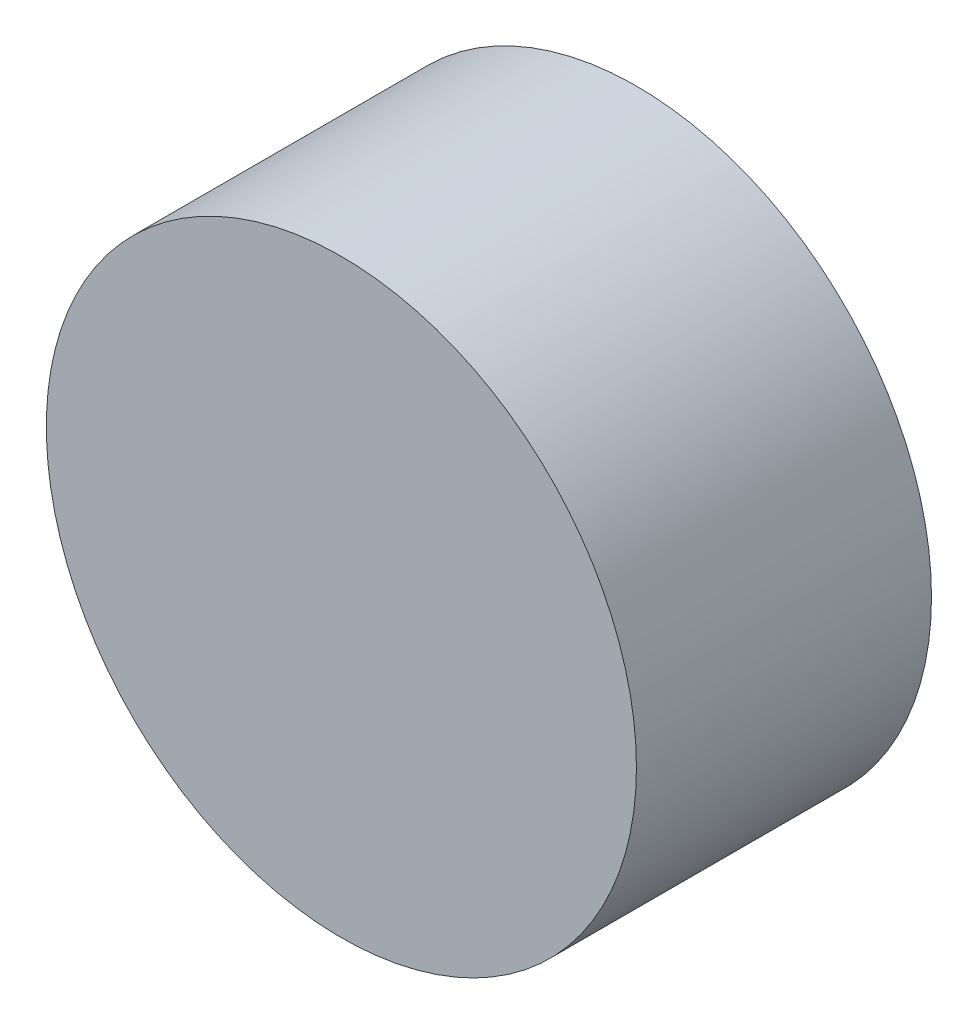
SolidWorks part; units mm, degrees
material "AISI 304"
ref_plane "Plan de face" through (0, 0, 0) normal (0, 0, 1) x (1, 0, 0)
ref_plane "Plan de dessus" through (0, 0, 0) normal (0, 1, 0) x (1, 0, 0)
ref_plane "Plan de droite" through (0, 0, 0) normal (1, 0, 0) x (0, 0, -1)
sketch "Esquisse1" plane through (0, 0, 0) normal (0, 0, 1) x (1, 0, 0)
  circle A0 centre (0, 0) radius 3
  dimension "D1" = 6
extrude "Main" add sketch "Esquisse1" along normal blind 3
